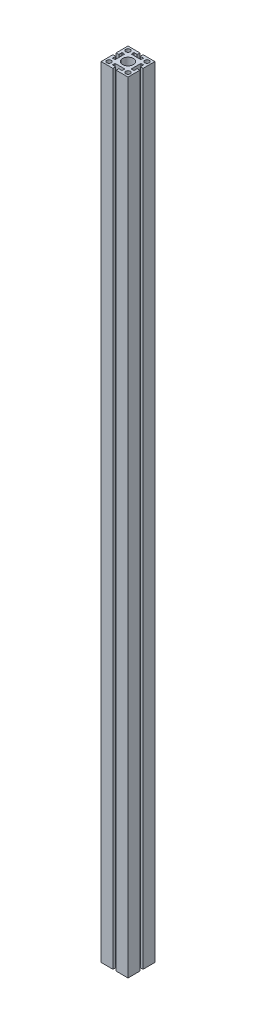
SolidWorks part; units mm, degrees
ref_plane "Front Plane" through (0, 0, 0) normal (0, 0, 1) x (1, 0, 0)
ref_plane "Top Plane" through (0, 0, 0) normal (0, 1, 0) x (1, 0, 0)
ref_plane "Right Plane" through (0, 0, 0) normal (1, 0, 0) x (0, 0, -1)
sketch "Sketch1" plane through (0, 0, 0) normal (0, 1, 0) x (1, 0, 0)
  line L1 (-25, -3) -> (-25, -25)
  line L6 (9, 20) -> (9, 15)
  line L7 (9, 20) -> (3, 20)
  line L8 (9, 15) -> (-9, 15)
  line L9 (3, 20) -> (3, 25)
  line L10 (-3, 25) -> (-25, 25)
  line L11 (-25, 25) -> (-25, 3)
  line L12 (-25, -25) -> (-3, -25)
  line L13 (25, -25) -> (25, -3)
  line L14 (3, 25) -> (25, 25)
  line L15 (-3, 20) -> (-3, 25)
  line L16 (-9, 20) -> (-9, 15)
  line L17 (3, -25) -> (25, -25)
  line L18 (25, 3) -> (25, 25)
  line L19 (-3, 20) -> (-9, 20)
  line L21 (-20, 9) -> (-15, 9)
  line L22 (-20, 9) -> (-20, 3)
  line L24 (-15, 9) -> (-15, -9)
  line L27 (-20, 3) -> (-25, 3)
  line L28 (20, -9) -> (15, -9)
  line L29 (20, -9) -> (20, -3)
  line L30 (15, -9) -> (15, 9)
  line L31 (20, -3) -> (25, -3)
  line L32 (20, 3) -> (25, 3)
  line L33 (-20, -3) -> (-25, -3)
  line L34 (20, 9) -> (15, 9)
  line L35 (20, 3) -> (20, 9)
  line L40 (-20, -9) -> (-15, -9)
  line L41 (-20, -3) -> (-20, -9)
  line L42 (-9, -20) -> (-9, -15)
  line L43 (-9, -20) -> (-3, -20)
  line L44 (-9, -15) -> (9, -15)
  line L45 (-3, -20) -> (-3, -25)
  line L46 (3, -20) -> (3, -25)
  line L47 (9, -20) -> (9, -15)
  line L48 (3, -20) -> (9, -20)
  circle A0 centre (0, 0) radius 10
  circle A1 centre (-17.6777, 17.6777) radius 4.1387
  circle A2 centre (17.6777, 17.6777) radius 4.1387
  circle A3 centre (17.6777, -17.6777) radius 4.1387
  circle A4 centre (-17.6777, -17.6777) radius 4.1387
  point P44 (0, 0)
  point P46 (0, 0)
  dimension "D1" = 4
extrude "Boss-Extrude1" add sketch "Sketch1" along normal blind 1450
